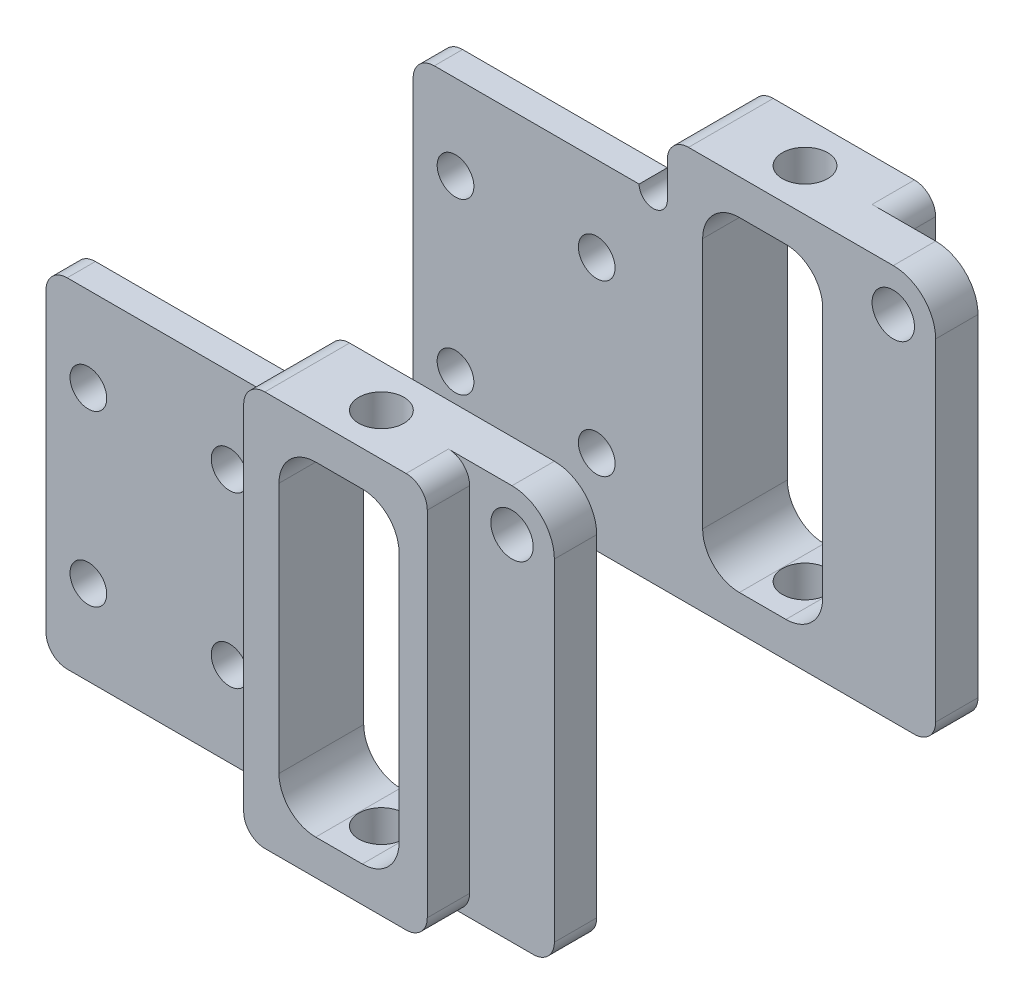
SolidWorks part; units mm, degrees
material "6061 合金"
ref_plane "前视基准面" through (0, 0, 0) normal (0, 0, 1) x (1, 0, 0)
ref_plane "上视基准面" through (0, 0, 0) normal (0, 1, 0) x (1, 0, 0)
ref_plane "右视基准面" through (0, 0, 0) normal (1, 0, 0) x (0, 0, -1)
sketch "草图2" plane through (0, 0, 0) normal (0, 0, 1) x (1, 0, 0)
  line L0 (-40, 24) -> (40, 24)
  line L1 (-20, -20) -> (20, -20)
  line L2 (-20, -20) -> (-20, 20)
  line L3 (-20, 20) -> (20, 20)
  line L4 (20, -20) -> (20, 20)
  line L5 (-20, -20) -> (20, 20) construction
  line L6 (-20, 20) -> (20, -20) construction
  line L7 (-40, -35) -> (40, -35)
  line L8 (-40, -35) -> (-40, 25)
  line L9 (-40, 25) -> (40, 25)
  line L10 (40, -35) -> (40, 25)
  line L11 (-40, -35) -> (40, 25) construction
  line L12 (-40, 25) -> (40, -35) construction
  line L13 (-20, 19) -> (20, 19)
  point P0 (0, 0)
  point P6 (0, -5)
  dimension "D1" = 40
  dimension "D2" = 60
  dimension "D3" = 80
  dimension "D4" = 5
  dimension "D5" = 40
  dimension "D6" = 1
  dimension "D7" = 1
sketch "草图3" plane through (0, 0, 0) normal (0, 0, 1) x (1, 0, 0)
  line L0 (2, 19) -> (2, -5)
  line L1 (2, -5) -> (20, -5)
  line L2 (-40, 24) -> (40, 24) construction
  line L3 (20, -20) -> (20, 20) construction
  line L4 (-20, 13) -> (20, 13) construction
  line L5 (-20, -20) -> (-20, 20) construction
  line L6 (-20, 19) -> (20, 19) construction
  line L7 (20, -5) -> (39, -5)
  line L8 (39, -5) -> (39, 20)
  line L9 (2, 19) -> (20, 19)
  line L10 (20, 19) -> (20, 23)
  line L11 (20, 23) -> (36, 23)
  line L12 (-20, 20) -> (20, 20) construction
  circle A0 centre (36, 20) radius 1.5
  circle A1 centre (36, 20) radius 4 construction
  circle A2 centre (15, 13) radius 1.3
  circle A3 centre (5, 13) radius 1.3
  circle A4 centre (36, 20) radius 3 construction
  arc A5 (36, 23) -> (39, 20) centre (36, 20) cw
  circle A6 centre (5, 1) radius 1.3
  circle A7 centre (15, 1) radius 1.3
  dimension "D1" = 8
  dimension "D2" = 3
  dimension "D3" = 16
  dimension "D5" = 5
  dimension "D6" = 10
  dimension "D7" = 2.6
  dimension "D8" = 2.6
  dimension "D9" = 6
  dimension "D12" = 12
  dimension "D13" = 2.6
  dimension "D14" = 2.6
  dimension "D15" = 12
  dimension "D4" = 6
  dimension "D10" = 25
  dimension "D11" = 18
extrude "凸台-拉伸1" add sketch "草图3" along normal blind 2
sketch "草图4" plane through (0, 0, 2) normal (0, 0, 1) x (1, 0, 0)
  line L0 (39, -5) -> (20, -5)
  line L2 (20, -5) -> (20, 23)
  line L3 (20, 23) -> (36, 23)
  line L4 (39, -5) -> (39, 20)
  arc A0 (36, 23) -> (39, 20) centre (36, 20) cw
  circle A1 centre (36, 20) radius 1.5
extrude "凸台-拉伸2" add sketch "草图4" along normal blind 4
sketch "草图5" plane through (0, 23, 0) normal (0, 1, 0) x (1, 0, 0)
  line L0 (20, -6) -> (20, 0) construction
  line L1 (-40, 0) -> (40, 0) construction
  circle A0 centre (26.75, -3) radius 1.6
  dimension "D1" = 6.75
  dimension "D2" = 3
  dimension "D3" = 3.2
extrude "切除-拉伸1" cut sketch "草图5" against normal blind 34
sketch "草图6" plane through (0, 0, 6) normal (0, 0, 1) x (1, 0, 0)
  line L0 (20, 23) -> (20, -5) construction
  line L1 (22.5, 20.5) -> (31, 20.5)
  line L2 (22.5, 20.5) -> (22.5, -2.5)
  line L3 (22.5, -2.5) -> (31, -2.5)
  line L4 (31, 20.5) -> (31, -2.5)
  line L5 (36, 23) -> (20, 23) construction
  line L6 (20, -5) -> (39, -5) construction
  dimension "D1" = 8.5
  dimension "D2" = 2.5
  dimension "D3" = 2.5
  dimension "D4" = 2.5
extrude "切除-拉伸2" cut sketch "草图6" against normal blind 34
fillet "圆角1" radius 2.6 4 edges at (31, 20.5, 3) (31, -2.5, 3) (22.5, -2.5, 3) (22.5, 20.5, 3)
sketch "草图7" plane through (0, 0, 6) normal (0, 0, 1) x (1, 0, 0)
  line L0 (33, 23) -> (33, -5)
  line L1 (36, 23) -> (20, 23) construction
  line L2 (20, -5) -> (39, -5) construction
  line L3 (33, -5) -> (39, -5)
  line L4 (39, -5) -> (39, 20)
  line L5 (33, 23) -> (36, 23)
  arc A0 (36, 23) -> (39, 20) centre (36, 20) cw
  dimension "D1" = 6
extrude "切除-拉伸3" cut sketch "草图7" against normal blind 3
fillet "圆角2" radius 1.5 7 edges at (2, 19, 1) (2, -5, 1) (20, -5, 4) (39, -5, 1.5) (33, -5, 4.5) (33, 23, 4.5) (20, 23, 3)
sketch "草图10" plane through (0, 0, 2) normal (0, 0, 1) x (1, 0, 0)
  line L0 (-20, 19) -> (20, 19) construction
  circle A0 centre (19, 19) radius 1
  dimension "D1" = 2
extrude "切除-拉伸4" cut sketch "草图10" against normal blind 4
ref_plane "基准面4" through (0, 0, -12) normal (0, 0, -1) x (-1, 0, 0)
mirror "镜向1" about plane through (0, 0, -12) normal (0, 0, -1) of bodies 106
